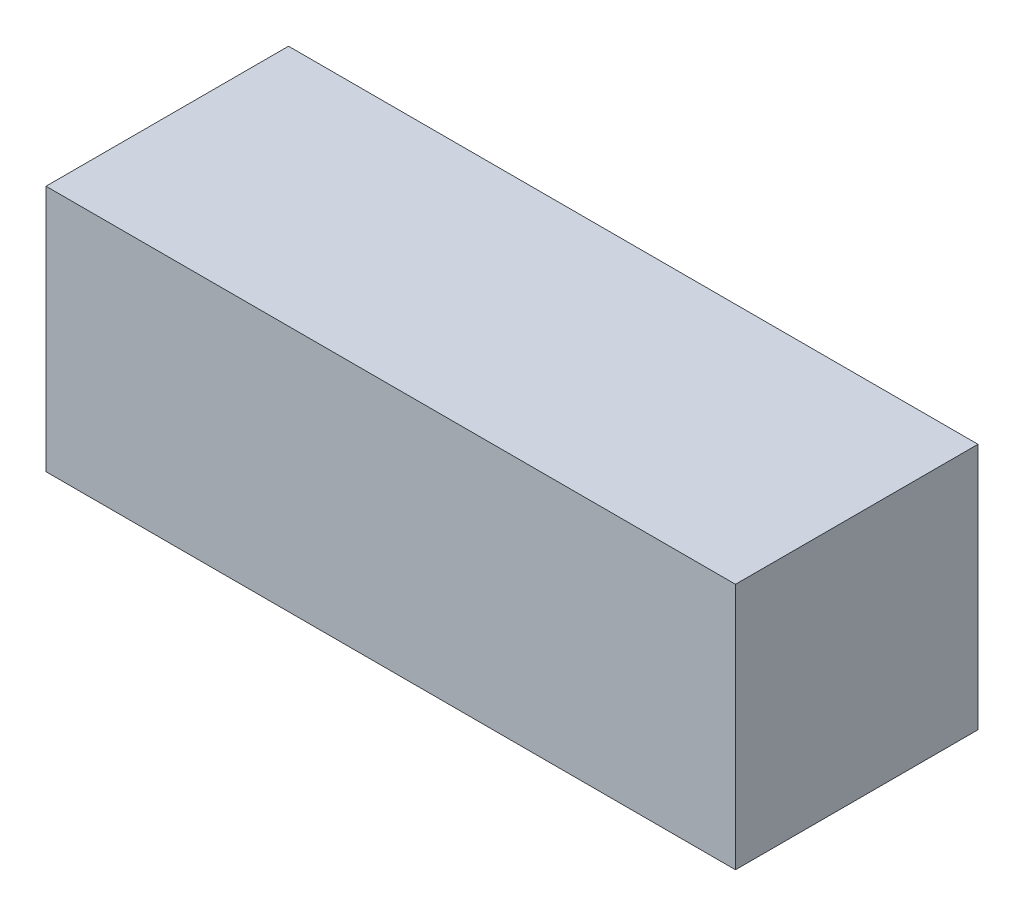
SolidWorks part; units mm, degrees
ref_plane "Front Plane" through (0, 0, 0) normal (0, 0, 1) x (1, 0, 0)
ref_plane "Top Plane" through (0, 0, 0) normal (0, 1, 0) x (1, 0, 0)
ref_plane "Right Plane" through (0, 0, 0) normal (1, 0, 0) x (0, 0, -1)
sketch "Sketch1" plane through (0, 0, 0) normal (0, 1, 0) x (1, 0, 0)
  line L1 (-72.5, 25.4999) -> (72.5, 25.4999)
  line L2 (-72.5, 25.4999) -> (-72.5, -25.4999)
  line L3 (-72.5, -25.4999) -> (72.5, -25.4999)
  line L4 (72.5, 25.4999) -> (72.5, -25.4999)
  line L5 (-72.5, 25.4999) -> (72.5, -25.4999) construction
  line L6 (-72.5, -25.4999) -> (72.5, 25.4999) construction
  point P0 (0, 0)
  dimension "D1" = 145
  dimension "D2" = 50.9999
extrude "Boss-Extrude1" add sketch "Sketch1" along normal blind 51.9999
